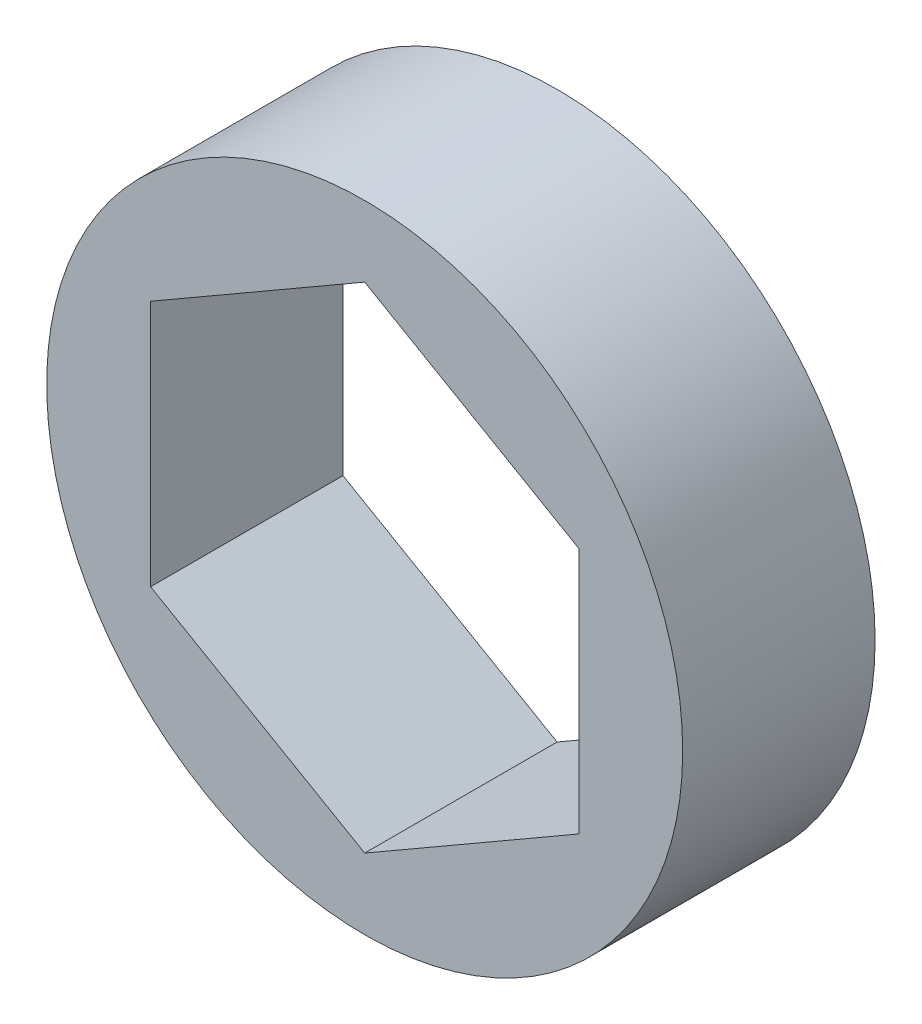
SolidWorks part; units mm, degrees
material "PET"
ref_plane "Front Plane" through (0, 0, 0) normal (0, 0, 1) x (1, 0, 0)
ref_plane "Top Plane" through (0, 0, 0) normal (0, 1, 0) x (1, 0, 0)
ref_plane "Right Plane" through (0, 0, 0) normal (1, 0, 0) x (0, 0, -1)
sketch "Sketch1" plane through (0, 0, 0) normal (0, 0, 1) x (1, 0, 0)
  line L1 (0, 7.4057) -> (-6.4135, 3.7028)
  line L2 (-6.4135, 3.7028) -> (-6.4135, -3.7028)
  line L3 (-6.4135, -3.7028) -> (0, -7.4057)
  line L4 (0, -7.4057) -> (6.4135, -3.7028)
  line L5 (6.4135, -3.7028) -> (6.4135, 3.7028)
  line L6 (6.4135, 3.7028) -> (0, 7.4057)
  circle A0 centre (0, 0) radius 6.4135 construction
  circle A1 centre (0, 0) radius 9.525
  dimension "D1" = 12.827
  dimension "D2" = 19.05
extrude "Boss-Extrude1" add sketch "Sketch1" along normal mid plane 5.7633
